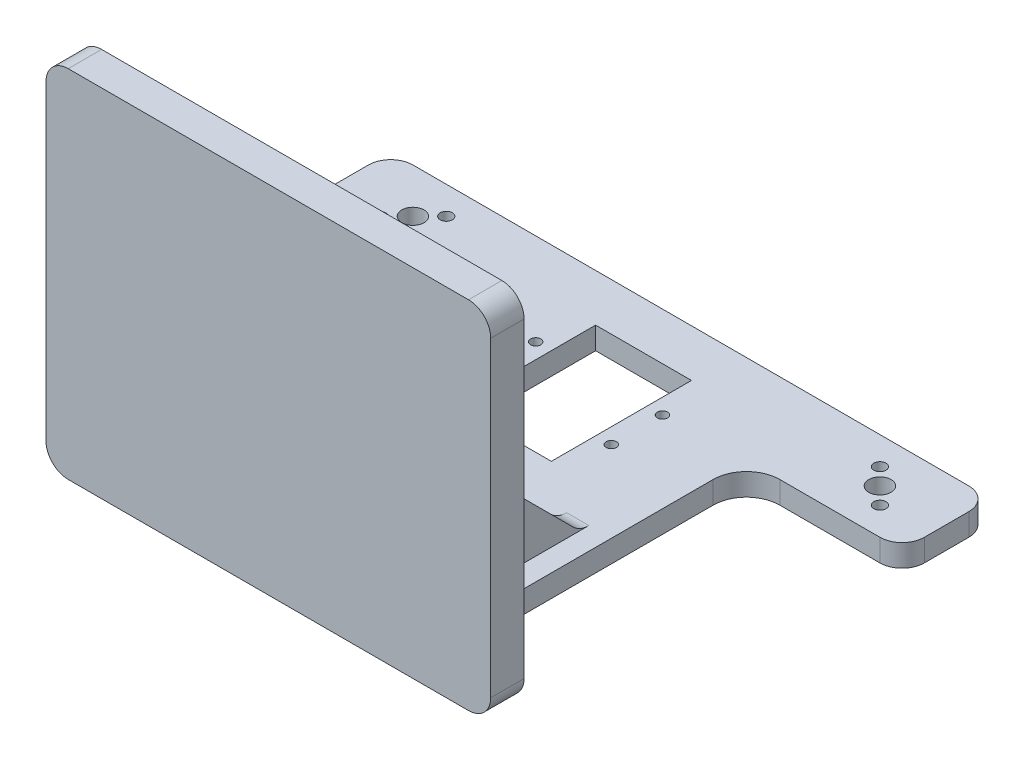
SolidWorks part; units mm, degrees
ref_plane "Vorne" through (0, 0, 0) normal (0, 0, 1) x (1, 0, 0)
ref_plane "Oben" through (0, 0, 0) normal (0, 1, 0) x (1, 0, 0)
ref_plane "Rechts" through (0, 0, 0) normal (1, 0, 0) x (0, 0, -1)
ref_plane "E_Boden" through (0, 1, 0) normal (0, 1, 0) x (1, 0, 0)
sketch "Skizze1" plane through (0, 0, 0) normal (0, 1, 0) x (1, 0, 0)
  line L0 (0, -133.037) -> (0, 127.1868) construction
  line L1 (-165.4867, 0) -> (188.3198, 0) construction
  line L2 (-125, 95) -> (125, 95)
  line L3 (-135, 85) -> (-135, 65)
  line L8 (-125, 55) -> (-80, 55)
  line L9 (-65, 40) -> (-65, -65)
  line L10 (-80, -80) -> (-90, -80)
  line L12 (-80, -95) -> (80, -95)
  line L14 (80, -80) -> (90, -80)
  line L15 (65, 40) -> (65, -65)
  line L16 (125, 55) -> (80, 55)
  line L17 (135, 85) -> (135, 65)
  line L18 (0, 75) -> (-166.9097, 75) construction
  line L19 (0, 82.5) -> (-150.2601, 82.5) construction
  line L20 (0, 67.5) -> (-143.7021, 67.5) construction
  line L21 (-112.5, 67.5) -> (-112.5, 109.8946) construction
  line L22 (-97.5, 82.5) -> (-97.5, 110.5565) construction
  line L23 (-105, 75) -> (-105, 35) construction
  line L24 (-105, 35) -> (-105, 140.5126) construction
  line L25 (-21.55, 73.71) -> (21.55, 73.71)
  line L26 (21.55, 73.71) -> (21.55, 10.71)
  line L27 (21.55, 10.71) -> (-21.55, 10.71)
  line L28 (-21.55, 10.71) -> (-21.55, 73.71)
  line L29 (0, 42.21) -> (-56.3168, 42.21) construction
  line L30 (-56.3168, 42.21) -> (55.721, 42.21) construction
  line L32 (-100, -95) -> (-80, -95)
  line L33 (80, -95) -> (100, -95)
  line L35 (-90, -80) -> (-100, -80)
  line L37 (90, -80) -> (100, -80)
  line L39 (-100, -80) -> (-100, -95)
  line L40 (100, -80) -> (100, -95)
  line L41 (-38.4535, 53.71) -> (31.8987, 53.71) construction
  arc A0 (65, 40) -> (80, 55) centre (80, 40) cw
  arc A1 (80, -80) -> (65, -65) centre (80, -65) cw
  arc A2 (-65, -65) -> (-80, -80) centre (-80, -65) cw
  arc A3 (-80, 55) -> (-65, 40) centre (-80, 40) cw
  arc A8 (-135, 65) -> (-125, 55) centre (-125, 65) ccw
  arc A9 (125, 55) -> (135, 65) centre (125, 65) ccw
  arc A10 (135, 85) -> (125, 95) centre (125, 85) ccw
  arc A11 (-125, 95) -> (-135, 85) centre (-125, 85) ccw
  circle A12 centre (-105, 75) radius 5
  circle A13 centre (105, 75) radius 5
  circle A14 centre (-97.5, 82.5) radius 2.75
  circle A15 centre (-112.5, 67.5) radius 2.75
  circle A16 centre (97.5, 82.5) radius 2.75
  circle A17 centre (112.5, 67.5) radius 2.75
  circle A18 centre (-28.5, 53.71) radius 2.3
  circle A19 centre (-28.5, 30.71) radius 2.3
  circle A20 centre (28.5, 30.71) radius 2.3
  circle A21 centre (28.5, 53.71) radius 2.3
  point P15 (0, -95)
  point P16 (0, 95)
  point P22 (65, 55)
  point P25 (65, -80)
  point P28 (-65, -80)
  point P31 (-65, 55)
  point P34 (100, -80)
  point P37 (100, -95)
  point P40 (-100, -95)
  point P43 (-100, -80)
  point P46 (-135, 55)
  point P49 (135, 55)
  point P52 (135, 95)
  point P55 (-135, 95)
  point P77 (0, 42.21)
  dimension "D7" = 15
  dimension "D8" = 10
  dimension "D9" = 10
  dimension "D13" = 5.5
  dimension "D14" = 5.5
  dimension "D20" = 4.6
  dimension "D21" = 20
  dimension "D1" = 270
  dimension "D2" = 40
  dimension "D3" = 150
  dimension "D4" = 200
  dimension "D5" = 130
  dimension "D6" = 15
  dimension "D10" = 210
  dimension "D11" = 15
  dimension "D12" = 7.5
  dimension "D15" = 15
  dimension "D16" = 7.5
  dimension "D17" = 32.79
  dimension "D18" = 43.1
  dimension "D19" = 63
  dimension "D22" = 28.5
extrude "Aufsatz-Linear austragen1" add sketch "Skizze1" along normal blind 10
sketch "Skizze2" plane through (0, 10, 0) normal (0, 1, 0) x (1, 0, 0)
sketch "Skizze3" plane through (0, 10, 0) normal (0, 1, 0) x (1, 0, 0)
  line L1 (-100, -80) -> (100, -80)
  line L2 (-100, -80) -> (-100, -95)
  line L3 (-100, -95) -> (100, -95)
  line L4 (100, -80) -> (100, -95)
extrude "Aufsatz-Linear austragen2" add sketch "Skizze3" along normal blind 150
fillet "Verrundung1" radius 10 4 edges at (100, 0, 87.5) (-100, 0, 87.5) (-100, 160, 87.5) (100, 160, 87.5)
ref_plane "Ebene1" through (-50, 0, 0) normal (-1, 0, 0) x (0, 0, 1)
sketch "Skizze5" plane through (-50, 0, 0) normal (-1, 0, 0) x (0, 0, 1)
  line L0 (10, 10) -> (80, 80)
  line L1 (-40, 10) -> (65, 10) construction
  line L2 (80, 150) -> (80, 10) construction
  line L3 (80, 80) -> (80, 10)
  line L4 (80, 10) -> (10, 10)
  dimension "D1" = 70
  dimension "D2" = 70
extrude "Aufsatz-Linear austragen3" add sketch "Skizze5" against normal blind 10
ref_plane "Ebene2" through (55, 0, 0) normal (1, 0, 0) x (0, 0, -1)
sketch "Skizze6" plane through (55, 0, 0) normal (1, 0, 0) x (0, 0, -1)
  line L0 (-10, 10) -> (-80, 80)
  line L1 (-80, 150) -> (-80, 10) construction
  line L2 (-80, 80) -> (-80, 10)
  line L3 (-80, 10) -> (-10, 10)
extrude "Aufsatz-Linear austragen4" add sketch "Skizze6" against normal blind 10
sketch "Skizze7" plane through (0, 10, 0) normal (0, 1, 0) x (1, 0, 0)
  line L0 (0, 73.71) -> (0, 10.71) construction
  line L1 (21.55, 73.71) -> (-21.55, 73.71) construction
  line L2 (-21.55, 10.71) -> (21.55, 10.71) construction
  line L3 (-21.55, 42.21) -> (21.55, 42.21) construction
  line L4 (-21.55, 73.71) -> (-21.55, 10.71) construction
  line L5 (21.55, 10.71) -> (21.55, 73.71) construction
  line L6 (-105, 58) -> (0, 25.21)
  line L7 (-105, 92) -> (4.9584, 58.4708)
  circle A0 centre (-105, 75) radius 17
  circle A1 centre (0, 42.21) radius 17
  dimension "D1" = 34
  dimension "D2" = 34
fillet "Verrundung2" radius 10 4 edges at (50, 10, 10) (50, 80, 80) (-45, 80, 80) (-45, 10, 10)
